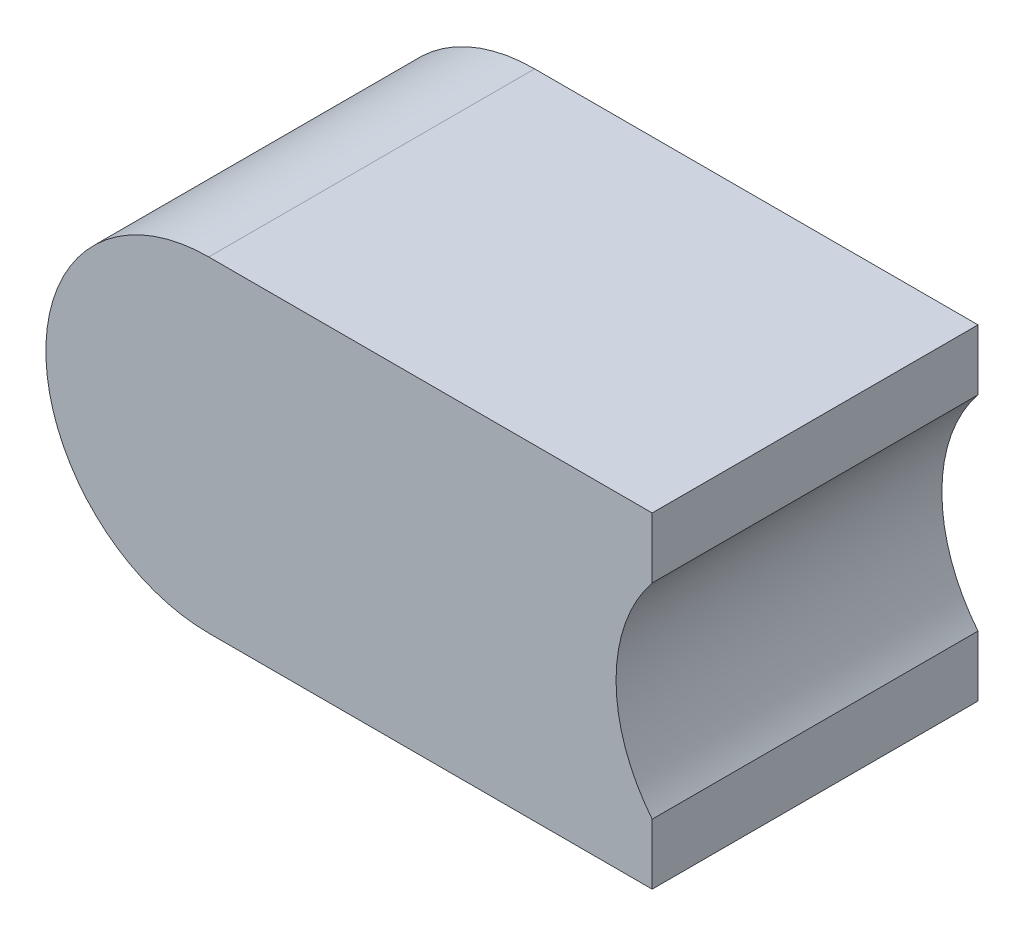
SolidWorks part; units mm, degrees
ref_plane "Front Plane" through (0, 0, 0) normal (0, 0, 1) x (1, 0, 0)
ref_plane "Top Plane" through (0, 0, 0) normal (0, 1, 0) x (1, 0, 0)
ref_plane "Right Plane" through (0, 0, 0) normal (1, 0, 0) x (0, 0, -1)
sketch "Sketch1" plane through (0, 0, 0) normal (0, 0, 1) x (1, 0, 0)
  line L1 (0, 0) -> (69.13, 0)
  line L3 (0, 50.8) -> (69.13, 50.8)
  line L10 (34.565, 50.8) -> (34.565, 0) construction
  line L11 (69.13, 0) -> (69.13, 9.453)
  line L12 (69.13, 41.347) -> (69.13, 50.8)
  arc A0 (69.13, 9.453) -> (69.13, 41.347) centre (88.9, 25.4) cw
  arc A1 (0, 50.8) -> (0, 0) centre (0, 25.4) ccw
  dimension "D1" = 50.8
extrude "Boss-Extrude1" add sketch "Sketch1" along normal blind 50.8
